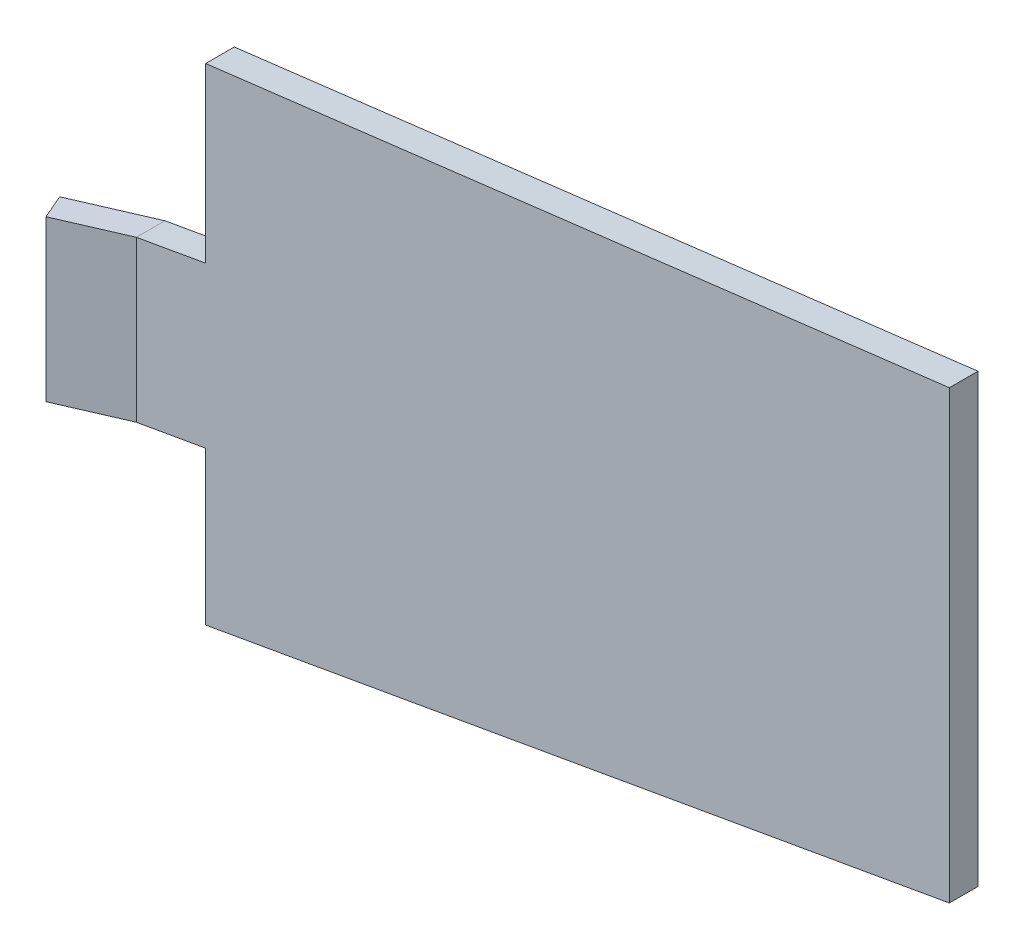
SolidWorks part; units mm, degrees
material "AISI 4340 Aço recozido"
ref_plane "Plano frontal" through (0, 0, 0) normal (0, 0, 1) x (1, 0, 0)
ref_plane "Plano superior" through (0, 0, 0) normal (0, 1, 0) x (1, 0, 0)
ref_plane "Plano direito" through (0, 0, 0) normal (1, 0, 0) x (0, 0, -1)
sketch "Esboço1" plane through (0, 0, 0) normal (0, 0, 1) x (1, 0, 0)
  line L0 (0, 85) -> (0, 0)
  line L1 (130, 100.9225) -> (0, 85)
  line L2 (130, 22.9225) -> (130, 100.9225)
  line L3 (0, 0) -> (130, 22.9225)
  dimension "D1" = 85
  dimension "D2" = 80
  dimension "D3" = 130
  dimension "D4" = 130
  dimension "D5" = 78
extrude "Ressalto-extrusão1" add sketch "Esboço1" along normal blind 5
sketch "Esboço3" plane through (0, 0, 5) normal (0, 0, 1) x (1, 0, 0)
  line L0 (-12.1131, 52.6399) -> (0, 54.7758)
  line L1 (-12.1131, 24.6399) -> (-12.1131, 52.6399)
  line L2 (0, 26.7758) -> (-12.1131, 24.6399)
  line L3 (0, 54.7758) -> (0, 26.7758)
  line L4 (0, 85) -> (0, 0) construction
  line L5 (130, 100.9225) -> (0, 85) construction
  point P6 (0, 0)
  dimension "D1" = 12.3
  dimension "D2" = 28
  dimension "D3" = 30
  dimension "D4" = 80
extrude "Ressalto-extrusão2" add sketch "Esboço3" against normal blind 5
ref_plane "Plano2" through (-12.0155, 0, 5.2245) normal (-0.9171, 0, 0.3987) x (0, -1, 0)
sketch "Esboço4" plane through (-12.0155, 0, 5.2245) normal (-0.9171, 0, 0.3987) x (0, -1, 0)
  line L0 (-52.6399, -0.2448) -> (-24.6399, -0.2448)
  line L1 (-24.6399, -0.2448) -> (-24.6399, -4.8301)
  line L2 (-24.6399, -4.8301) -> (-52.6399, -4.8301)
  line L3 (-52.6399, -4.8301) -> (-52.6399, -0.2448)
extrude "Ressalto-extrusão3" add sketch "Esboço4" along normal blind 12 and the other way up to vertex (1.9937 mm away)
